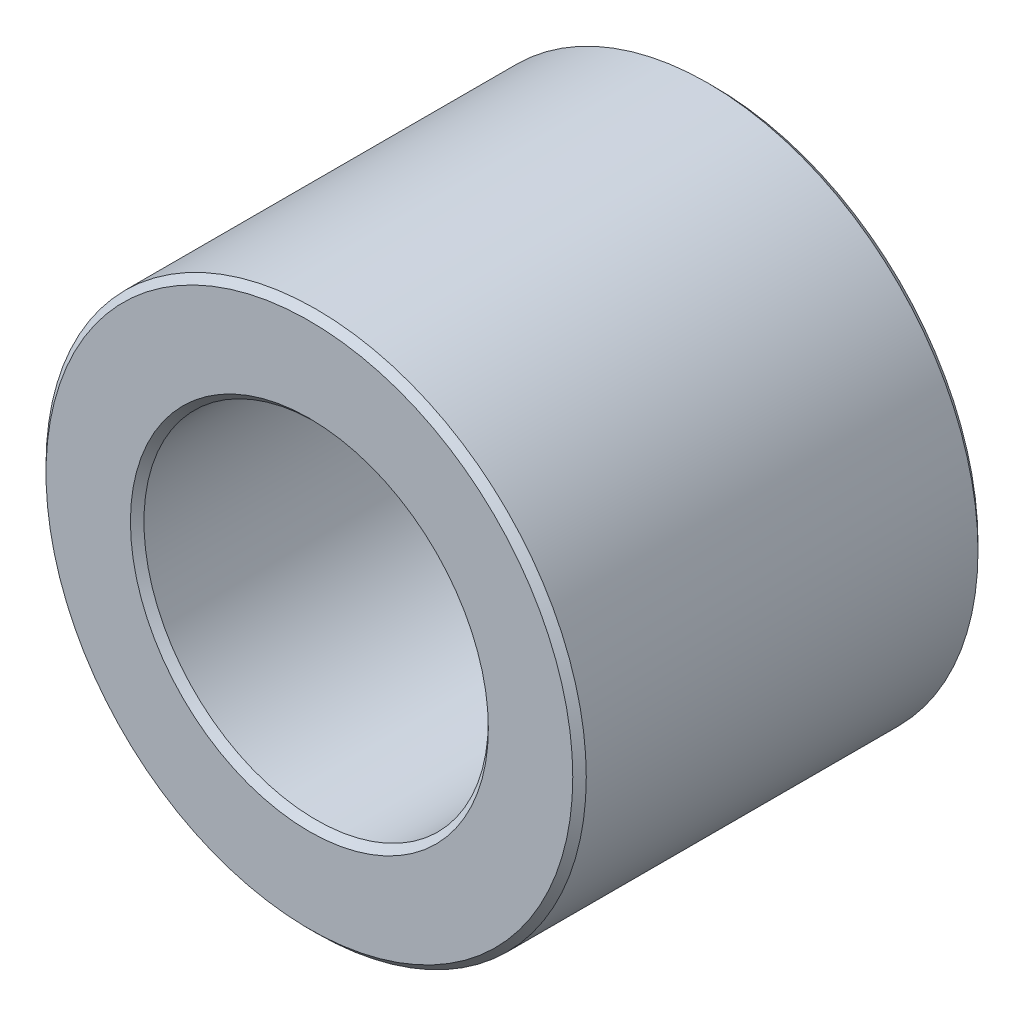
SolidWorks part; units mm, degrees
material "3003 Alloy"
ref_plane "Plano frontal" through (0, 0, 0) normal (0, 0, 1) x (1, 0, 0)
ref_plane "Plano superior" through (0, 0, 0) normal (0, 1, 0) x (1, 0, 0)
ref_plane "Plano direito" through (0, 0, 0) normal (1, 0, 0) x (0, 0, -1)
sketch "Esboço1" plane through (0, 0, 0) normal (0, 0, 1) x (1, 0, 0)
  circle A0 centre (0, 0) radius 2.55
  circle A1 centre (0, 0) radius 4
  dimension "D1" = 5.1
extrude "Ressalto-extrusão1" add sketch "Esboço1" along normal blind 6
chamfer "Chanfro1" distance 0.1 angle 45
